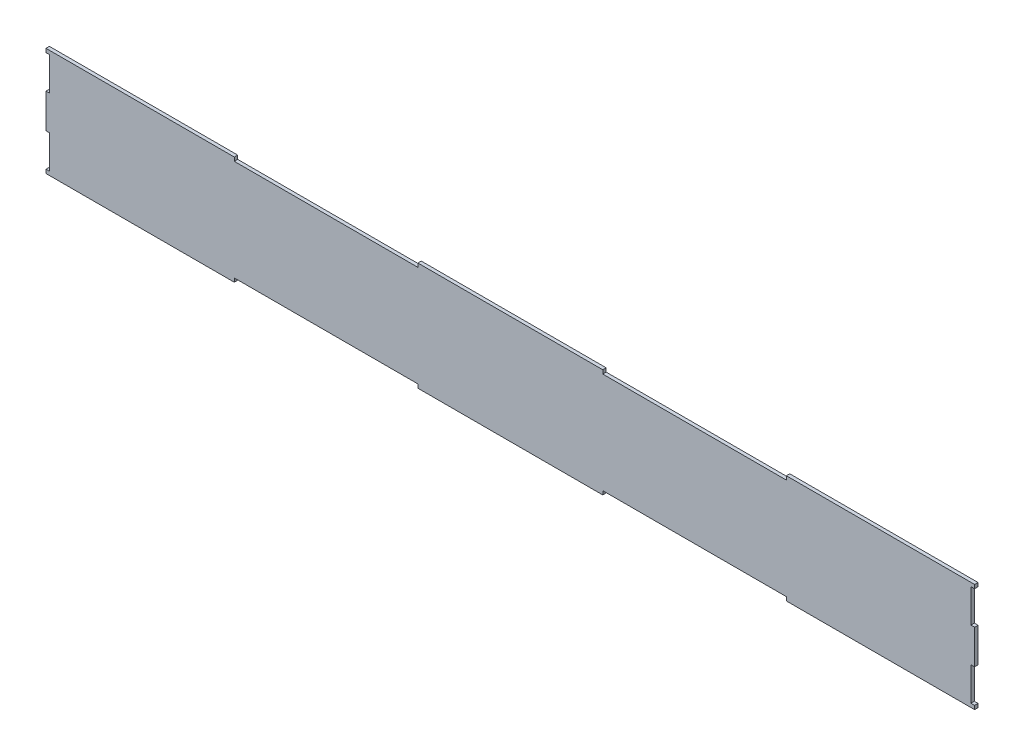
SolidWorks part; units mm, degrees
ref_plane "Front Plane" through (0, 0, 0) normal (0, 0, 1) x (1, 0, 0)
ref_plane "Top Plane" through (0, 0, 0) normal (0, 1, 0) x (1, 0, 0)
ref_plane "Right Plane" through (0, 0, 0) normal (1, 0, 0) x (0, 0, -1)
sketch "Sketch1" plane through (0, 0, 0) normal (0, 0, 1) x (1, 0, 0)
  line L0 (-218.4267, 25.51) -> (-216.6667, 25.51)
  line L1 (0, 0) -> (-216.6667, 0)
  line L2 (-43.4933, 25.51) -> (43.4933, 25.51)
  line L3 (-43.4933, 23.75) -> (-129.84, 23.75)
  line L4 (-216.6667, 8.0767) -> (-216.6667, 23.75)
  line L5 (-216.6667, 23.75) -> (-218.4267, 23.75)
  line L6 (-129.84, 23.75) -> (-129.84, 25.51)
  line L7 (-216.6667, 25.51) -> (-129.84, 25.51)
  line L8 (-218.4267, 23.75) -> (-218.4267, 25.51)
  line L9 (-216.6667, 0) -> (-218.4267, 0)
  line L10 (43.4933, 25.51) -> (43.4933, 23.75)
  line L11 (-216.6667, 8.0767) -> (-218.4267, 8.0767)
  line L12 (-218.4267, 0) -> (-218.4267, 8.0767)
  line L13 (43.4933, 23.75) -> (129.84, 23.75)
  line L14 (129.84, 23.75) -> (129.84, 25.51)
  line L16 (-43.4933, 23.75) -> (-43.4933, 25.51)
  line L17 (129.84, 25.51) -> (216.6667, 25.51)
  line L18 (218.4267, 25.51) -> (218.4267, 23.75)
  line L19 (218.4267, 23.75) -> (216.6667, 23.75)
  line L20 (216.6667, 23.75) -> (216.6667, 8.0767)
  line L21 (216.6667, 8.0767) -> (218.4267, 8.0767)
  line L22 (218.4267, 8.0767) -> (218.4267, 0)
  line L23 (218.4267, 0) -> (216.6667, 0)
  line L24 (216.6667, 0) -> (0, 0)
  line L25 (216.6667, 25.51) -> (218.4267, 25.51)
  point P15 (-216.6667, 25.51)
  dimension "D3" = 216.6667
  dimension "D4" = 1.76
  dimension "D5" = 8.0767
  dimension "D2" = 23.75
  dimension "D1" = 86.3467
  dimension "D6" = 86.9867
  dimension "D7" = 86.8267
extrude "Boss-Extrude1" add sketch "Sketch1" along normal blind 1.6
mirror "Mirror4" about plane through (0, 0, 1.6) normal (0, 1, 0) of "Boss-Extrude1"
equation "\"thinkness\"= \"epaisseur\""
equation "\"largeur\"= \"nbCarre\" * \"Coté\""
equation "\"hauteur\"= 47.5"
equation "\"D2@Sketch1\"=\"hauteur\"/2"
equation "\"D4@Sketch1\" = \"thinkness\" + \"jeu\""
equation "\"D3@Sketch1\"= \"largeur\" / 2"
equation "\"D5@Sketch1\" = \"hauteur\" / 6 + \"jeu\""
equation "\"D1@Boss-Extrude1\"= \"thinkness\""
equation "\"longueur\"= \"nbCarre\" * \"Coté\""
equation "\"jeu\"= 0.16"
equation "\"D1@Sketch1\" = \"largeur\" / 5 - 2 * \"jeu\""
equation "\"D6@Sketch1\"= \"largeur\" / 5 + 2 * \"jeu\""
equation "\"D7@Sketch1\"= \"largeur\" / 5 + \"jeu\""
equation "\"Coté\"= 33.333333"
equation "\"nbCarre\"= 13"
equation "\"epaisseur\"= 1.6"
equation "\"rapportEncoche\"= 0.5"
